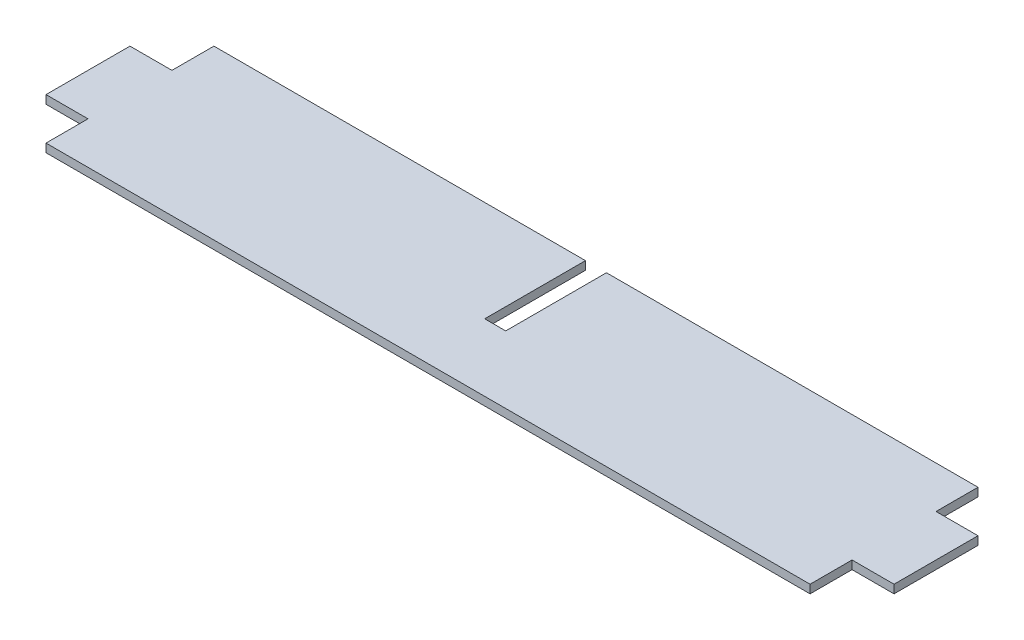
SolidWorks part; units mm, degrees
ref_plane "Front" through (0, 0, 0) normal (0, 0, 1) x (1, 0, 0)
ref_plane "Top" through (0, 0, 0) normal (0, 1, 0) x (1, 0, 0)
ref_plane "Right" through (0, 0, 0) normal (1, 0, 0) x (0, 0, -1)
sketch "Sketch1" plane through (0, 0, 0) normal (0, 1, 0) x (1, 0, 0)
  line L0 (0, 194.6839) -> (0, -206.1782) construction
  line L1 (505, 100) -> (-505, 100)
  line L2 (-505, 100) -> (-505, -100)
  line L3 (-505, -100) -> (505, -100)
  line L4 (505, 100) -> (505, -100)
  point P10 (0, -100)
  point P11 (0, 100)
  dimension "D1" = 505
  dimension "D2" = 200
  dimension "D3" = 100
extrude "Boss-Extrude1" add sketch "Sketch1" along normal blind 10
sketch "Sketch2" plane through (0, 10, 0) normal (0, 1, 0) x (1, 0, 0)
  line L0 (0, 323.8845) -> (0, -286.3006) construction
  line L1 (-573.7067, 0) -> (598.0256, 0) construction
  line L2 (-455, 100) -> (-455, 50)
  line L3 (505, 100) -> (-505, 100) construction
  line L4 (-455, 50) -> (-505, 50)
  line L5 (-505, 50) -> (-505, 100)
  line L6 (-505, 100) -> (-505, -100) construction
  line L7 (-505, 100) -> (-455, 100)
  dimension "D1" = 50
extrude "Cut-Extrude1" cut sketch "Sketch2" against normal blind 10
mirror "Mirror1" about plane through (0, 0, 0) normal (0, 0, 1) of "Cut-Extrude1"
mirror "Mirror2" about plane through (0, 0, 0) normal (1, 0, 0) of "Cut-Extrude1", "Mirror1"
sketch "Sketch3" plane through (0, 0, 0) normal (0, 1, 0) x (1, 0, 0)
  line L5 (0, 181.1972) -> (0, -170.2591) construction
  line L6 (12.5, 100) -> (-12.5, 100)
  line L7 (455, 100) -> (-455, 100) construction
  line L8 (-12.5, 100) -> (-12.5, -20)
  line L9 (-12.5, -20) -> (12.5, -20)
  line L10 (12.5, 100) -> (12.5, -20)
  point P10 (0, -20)
  point P11 (0, 100)
  dimension "D1" = 12.5
  dimension "D2" = 120
extrude "Cut-Extrude3" cut sketch "Sketch3" along normal blind 10
